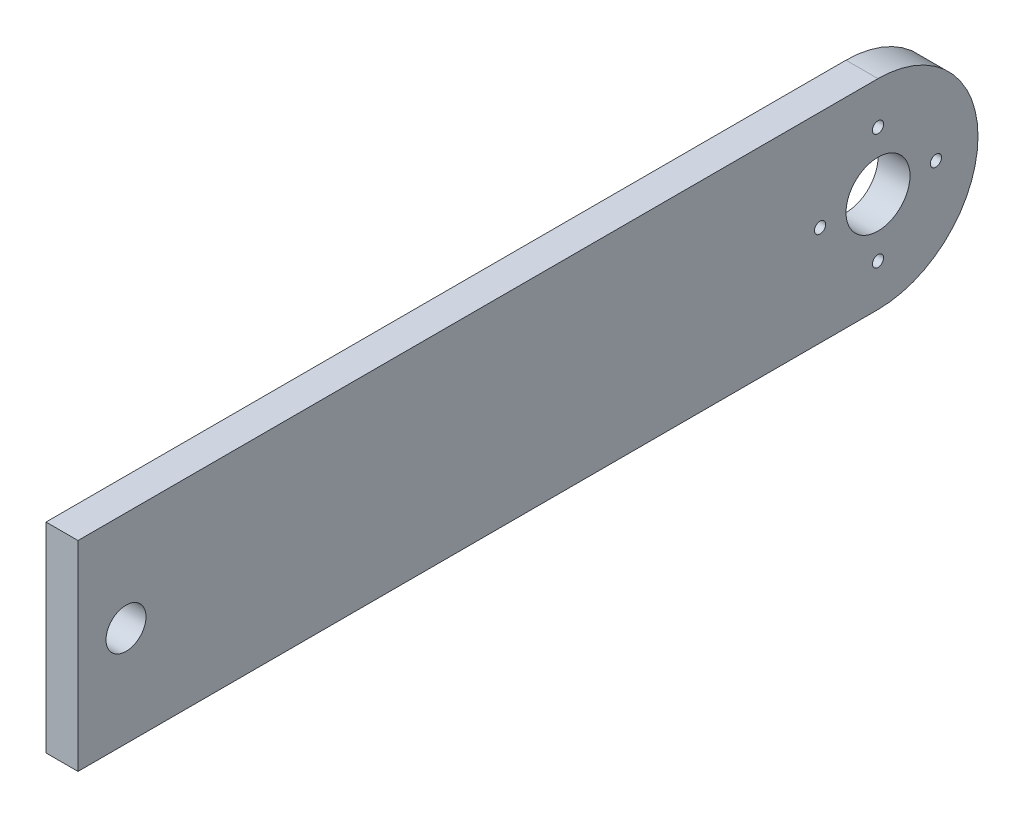
SolidWorks part; units mm, degrees
material "Perspex (TM) GS Acrylic Cast Sheet"
ref_plane "Front Plane" through (0, 0, 0) normal (0, 0, 1) x (1, 0, 0)
ref_plane "Top Plane" through (0, 0, 0) normal (0, 1, 0) x (1, 0, 0)
ref_plane "Right Plane" through (0, 0, 0) normal (1, 0, 0) x (0, 0, -1)
sketch "Sketch1" plane through (0, 0, 0) normal (1, 0, 0) x (0, 0, -1)
  line L0 (-100, 12.5) -> (-100, -12.5)
  line L19 (-100, 12.5) -> (0, 12.5)
  line L20 (-100, -12.5) -> (0, -12.5)
  circle A0 centre (0, 0) radius 4
  circle A1 centre (-7.24, 0) radius 0.7
  circle A2 centre (0, 7.24) radius 0.7
  circle A3 centre (7.24, 0) radius 0.7
  circle A4 centre (0, -7.24) radius 0.7
  arc A5 (0, -12.5) -> (0, 12.5) centre (0, 0) ccw
  point P18 (0, 0)
  dimension "D1" = 8
  dimension "D2" = 1.4
  dimension "D5" = 100
  dimension "D9" = 25
  dimension "D3" = 7.24
  dimension "D4" = 4
extrude "Boss-Extrude1" add sketch "Sketch1" along normal blind 4
sketch "Sketch2" plane through (4, 0, 0) normal (1, 0, 0) x (0, 0, -1)
  line L0 (0, 0) -> (-100, 0) construction
  line L1 (-100, 12.5) -> (-100, -12.5) construction
sketch "Sketch3" plane through (4, 0, 0) normal (1, 0, 0) x (0, 0, -1)
  line L0 (0, 0) -> (-100, 0) construction
  circle A0 centre (-94, 0) radius 2.5
  dimension "D2" = 5
  dimension "D1" = 94
extrude "Cut-Extrude1" cut sketch "Sketch3" against normal blind 10
